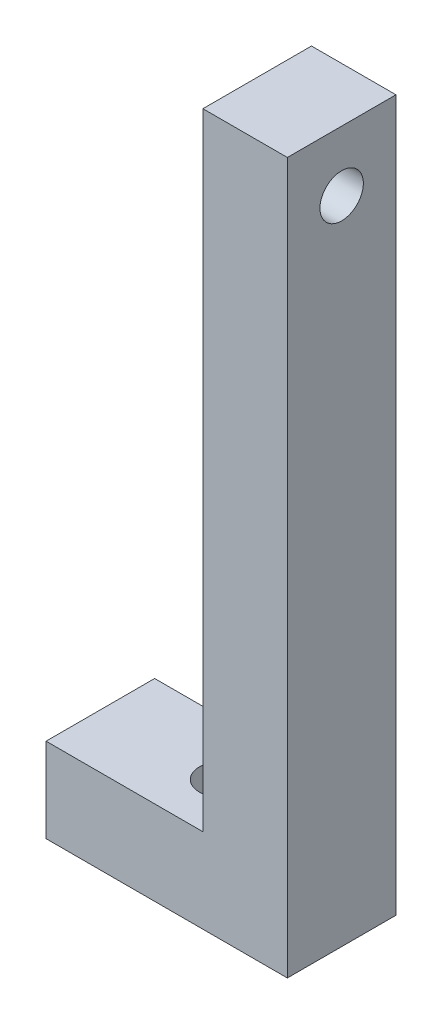
SolidWorks part; units mm, degrees
ref_plane "Plan de face" through (0, 0, 0) normal (0, 0, 1) x (1, 0, 0)
ref_plane "Plan de dessus" through (0, 0, 0) normal (0, 1, 0) x (1, 0, 0)
ref_plane "Plan de droite" through (0, 0, 0) normal (1, 0, 0) x (0, 0, -1)
sketch "Esquisse1" plane through (0, 0, 0) normal (0, 0, 1) x (1, 0, 0)
  line L0 (0, 0) -> (20, 0)
  line L1 (0, 0) -> (0, 7)
  line L2 (20, 0) -> (20, 7)
  line L3 (0, 7) -> (20, 7)
  line L5 (20, 7) -> (20, 58.9)
  line L6 (13, 7) -> (13, 58.9)
  line L7 (20, 58.9) -> (13, 58.9)
  point P0 (20, 12.6195)
  dimension "D1" = 58.9
  dimension "D2" = 20
  dimension "D3" = 7
  dimension "D4" = 7
extrude "Boss.-Extru.1" add sketch "Esquisse1" along normal blind 9 contours L3 L1 L0 L2 | L5 L7 L6 L3
sketch "Esquisse2" plane through (0, 7, 0) normal (0, 1, 0) x (1, 0, 0)
  line L0 (0, 0) -> (13, 0) construction
  line L1 (0, -9) -> (0, 0) construction
  circle A0 centre (10, -4.5) radius 1.8
  dimension "D1" = 3.6
  dimension "D2" = 4.5
  dimension "D3" = 10
extrude "Enlèv. mat.-Extru.1" cut sketch "Esquisse2" against normal blind 9
sketch "Esquisse3" plane through (13, 0, 0) normal (-1, 0, 0) x (0, 0, 1)
  line L0 (9, 7) -> (9, 58.9) construction
  line L2 (9, 58.9) -> (0, 58.9) construction
  circle A0 centre (4.5, 53.9) radius 1.8
  point P4 (0, 0)
  point P6 (-3.6137, 54.8054)
  dimension "D1" = 3.6
  dimension "D2" = 4.5
  dimension "D3" = 5
extrude "Enlèv. mat.-Extru.2" cut sketch "Esquisse3" against normal blind 9
